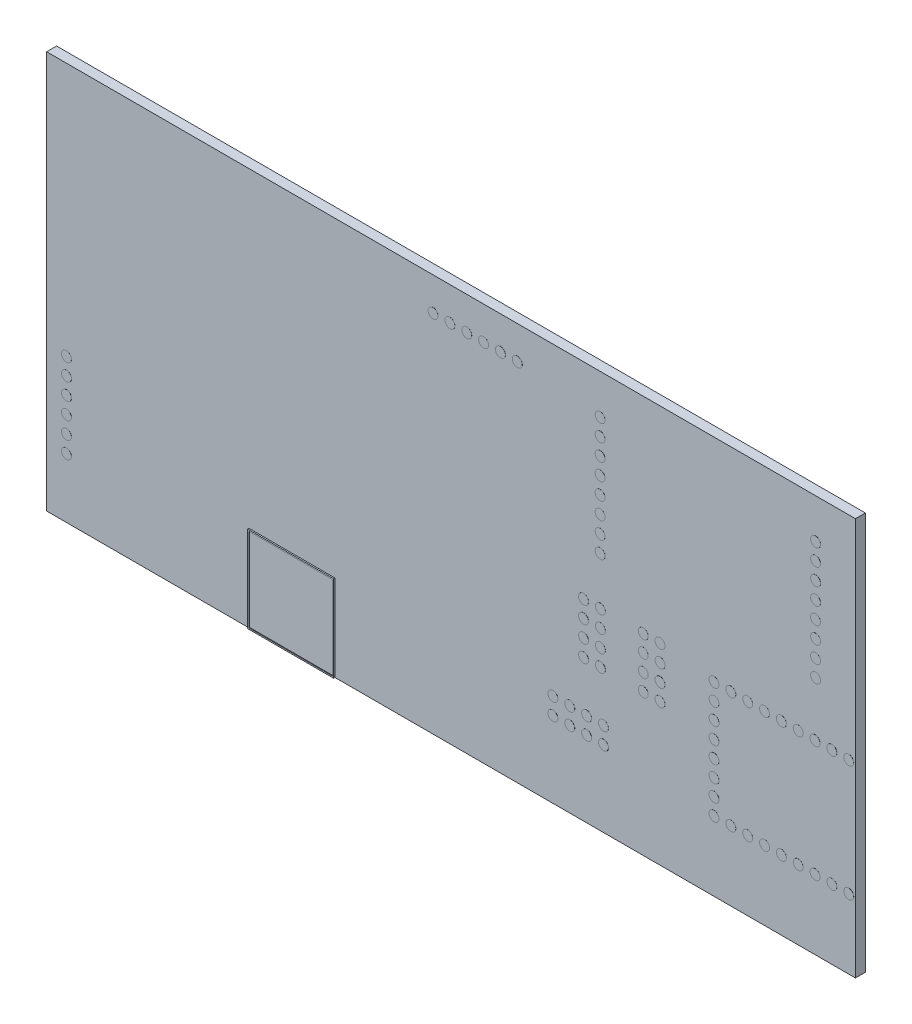
SolidWorks part; units mm, degrees
ref_plane "Front Plane" through (0, 0, 0) normal (0, 0, 1) x (1, 0, 0)
ref_plane "Top Plane" through (0, 0, 0) normal (0, 1, 0) x (1, 0, 0)
ref_plane "Right Plane" through (0, 0, 0) normal (1, 0, 0) x (0, 0, -1)
sketch "Sketch1" plane through (0, 0, 0) normal (0, 0, 1) x (1, 0, 0)
  line L1 (61, -30) -> (-61, -30)
  line L2 (61, -30) -> (61, 30)
  line L3 (61, 30) -> (-61, 30)
  line L4 (-61, -30) -> (-61, 30)
  line L5 (61, -30) -> (-61, 30) construction
  line L6 (61, 30) -> (-61, -30) construction
  point P0 (0, 0)
  dimension "D1" = 122
  dimension "D2" = 60
extrude "Boss-Extrude1" add sketch "Sketch1" along normal blind 1.5
sketch "Sketch2" plane through (0, 0, 1.5) normal (0, 0, 1) x (1, 0, 0)
  line L0 (61, -30) -> (61, 30) construction
  line L1 (61, 30) -> (-61, 30) construction
  line L2 (-61, -30) -> (61, -30) construction
  line L3 (-61, 30) -> (-61, -30) construction
  circle A0 centre (60, -2) radius 0.75
  circle A1 centre (57.46, -2) radius 0.75
  circle A2 centre (54.92, -2) radius 0.75
  circle A3 centre (52.38, -2) radius 0.75
  circle A4 centre (49.84, -2) radius 0.75
  circle A5 centre (47.3, -2) radius 0.75
  circle A6 centre (44.76, -2) radius 0.75
  circle A7 centre (42.22, -2) radius 0.75
  circle A8 centre (57.46, -19.5) radius 0.75
  circle A9 centre (54.92, -19.5) radius 0.75
  circle A10 centre (52.38, -19.5) radius 0.75
  circle A11 centre (49.84, -19.5) radius 0.75
  circle A12 centre (47.3, -19.5) radius 0.75
  circle A13 centre (44.76, -19.5) radius 0.75
  circle A14 centre (42.22, -19.5) radius 0.75
  circle A15 centre (60, -19.5) radius 0.75
  circle A16 centre (39.68, -2) radius 0.75
  circle A17 centre (39.68, -4.5) radius 0.75
  circle A18 centre (39.68, -7) radius 0.75
  circle A19 centre (39.68, -9.5) radius 0.75
  circle A20 centre (39.68, -12) radius 0.75
  circle A21 centre (39.68, -14.5) radius 0.75
  circle A22 centre (39.68, -17) radius 0.75
  circle A23 centre (39.68, -19.5) radius 0.75
  circle A24 centre (55, 24) radius 0.75
  circle A25 centre (22.5, 24) radius 0.75
  circle A26 centre (22.5, 21.46) radius 0.75
  circle A27 centre (22.5, 18.92) radius 0.75
  circle A28 centre (22.5, 16.38) radius 0.75
  circle A29 centre (22.5, 13.84) radius 0.75
  circle A30 centre (22.5, 11.3) radius 0.75
  circle A31 centre (22.5, 8.76) radius 0.75
  circle A32 centre (22.5, 6.22) radius 0.75
  circle A33 centre (55, 21.46) radius 0.75
  circle A34 centre (55, 18.92) radius 0.75
  circle A35 centre (55, 16.38) radius 0.75
  circle A36 centre (55, 13.84) radius 0.75
  circle A37 centre (55, 11.3) radius 0.75
  circle A38 centre (55, 8.76) radius 0.75
  circle A39 centre (55, 6.22) radius 0.75
  circle A40 centre (10, 25) radius 0.75
  circle A41 centre (7.46, 25) radius 0.75
  circle A42 centre (4.92, 25) radius 0.75
  circle A43 centre (2.38, 25) radius 0.75
  circle A44 centre (-0.16, 25) radius 0.75
  circle A45 centre (-2.7, 25) radius 0.75
  circle A46 centre (-58, -21) radius 0.75
  circle A47 centre (-58, -18.46) radius 0.75
  circle A48 centre (-58, -15.92) radius 0.75
  circle A49 centre (-58, -13.38) radius 0.75
  circle A50 centre (-58, -10.84) radius 0.75
  circle A51 centre (-58, -8.3) radius 0.75
  circle A52 centre (20, -1) radius 0.75
  circle A53 centre (22.54, -1) radius 0.75
  circle A54 centre (22.54, -3.54) radius 0.75
  circle A55 centre (22.54, -6.08) radius 0.75
  circle A56 centre (22.54, -8.62) radius 0.75
  circle A57 centre (20, -3.54) radius 0.75
  circle A58 centre (20, -6.08) radius 0.75
  circle A59 centre (20, -8.62) radius 0.75
  circle A60 centre (29, -1) radius 0.75
  circle A61 centre (31.54, -1) radius 0.75
  circle A62 centre (31.54, -3.54) radius 0.75
  circle A63 centre (29, -3.54) radius 0.75
  circle A64 centre (29, -6.08) radius 0.75
  circle A65 centre (29, -8.62) radius 0.75
  circle A66 centre (31.54, -8.62) radius 0.75
  circle A67 centre (31.54, -6.08) radius 0.75
  circle A68 centre (23, -16) radius 0.75
  circle A69 centre (20.46, -16) radius 0.75
  circle A70 centre (17.92, -16) radius 0.75
  circle A71 centre (15.38, -16) radius 0.75
  circle A72 centre (20.46, -18.54) radius 0.75
  circle A73 centre (17.92, -18.54) radius 0.75
  circle A74 centre (15.38, -18.54) radius 0.75
  circle A75 centre (23, -18.54) radius 0.75
  dimension "D2" = 1.5
  dimension "D6" = 1.5
  dimension "D9" = 1.5
  dimension "D14" = 1.5
  dimension "D18" = 1.5
  dimension "D22" = 1.5
  dimension "D28" = 1.5
  dimension "D1" = 1
  dimension "D3" = 32
  dimension "D7" = 2.54
  dimension "D10" = 6
  dimension "D11" = 6
  dimension "D15" = 5
  dimension "D16" = 51
  dimension "D19" = 9
  dimension "D20" = 3
  dimension "D23" = 29
  dimension "D24" = 41
  dimension "D29" = 38
  dimension "D30" = 14
  dimension "D4" = 8
  dimension "D5" = 2
  dimension "D8" = 8
  dimension "D12" = 2
  dimension "D13" = 8
  dimension "D17" = 6
  dimension "D21" = 6
  dimension "D25" = 2
  dimension "D26" = 4
  dimension "D27" = 2
  dimension "D31" = 4
  dimension "D32" = 2
extrude "Boss-Extrude2" add sketch "Sketch2" along normal blind 0.01
sketch "Sketch3" plane through (0, 0, 1.5) normal (0, 0, 1) x (1, 0, 0)
  line L0 (-61, -30) -> (61, -30) construction
  line L1 (-30.5, -17) -> (-17.5, -17)
  line L2 (-30.5, -17) -> (-30.5, -30)
  line L3 (-30.5, -30) -> (-17.5, -30)
  line L4 (-17.5, -17) -> (-17.5, -30)
  line L5 (-30.5, -17) -> (-17.5, -30) construction
  line L6 (-30.5, -30) -> (-17.5, -17) construction
  line L7 (-61, 30) -> (-61, -30) construction
  point P0 (-24, -23.5)
  dimension "D1" = 13
  dimension "D2" = 13
  dimension "D3" = 37
extrude "Boss-Extrude3" add sketch "Sketch3" along normal blind 0.1
sketch "Sketch4" plane through (0, 0, 1.6) normal (0, 0, 1) x (1, 0, 0)
  line L1 (-30.5, -17) -> (-17.5, -17)
  line L2 (-30.5, -17) -> (-30.5, -30)
  line L3 (-30.5, -30) -> (-17.5, -30)
  line L4 (-17.5, -17) -> (-17.5, -30)
  line L5 (-30.3, -17.2) -> (-17.7, -17.2)
  line L6 (-30.3, -17.2) -> (-30.3, -29.8)
  line L7 (-30.3, -29.8) -> (-17.7, -29.8)
  line L8 (-17.7, -17.2) -> (-17.7, -29.8)
  dimension "D1" = 0.2
  dimension "D2" = 0.2
  dimension "D3" = 0.2
  dimension "D4" = 0.2
extrude "Boss-Extrude4" add sketch "Sketch4" along normal blind 0.1
